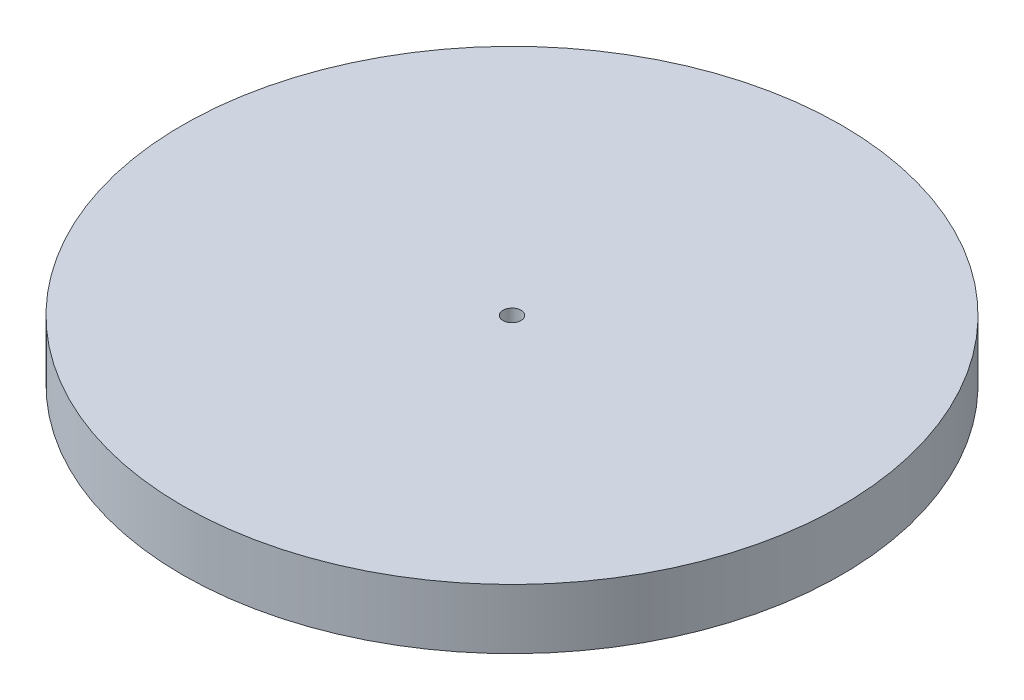
SolidWorks part; units mm, degrees
ref_plane "Front Plane" through (0, 0, 0) normal (0, 0, 1) x (1, 0, 0)
ref_plane "Top Plane" through (0, 0, 0) normal (0, 1, 0) x (1, 0, 0)
ref_plane "Right Plane" through (0, 0, 0) normal (1, 0, 0) x (0, 0, -1)
sketch "Sketch2" plane through (0, 0, 0) normal (0, 1, 0) x (1, 0, 0)
  circle A0 centre (0, 0) radius 12
  dimension "D1" = 24
extrude "Boss-Extrude1" add sketch "Sketch2" along normal blind 5
sketch "Sketch3" plane through (0, 5, 0) normal (0, 1, 0) x (1, 0, 0)
  circle A0 centre (0, 0) radius 0.75
  dimension "D1" = 1.5
extrude "Cut-Extrude1" cut sketch "Sketch3" against normal blind 5
sketch "Sketch4" plane through (0, 5, 0) normal (0, 1, 0) x (1, 0, 0)
  circle A0 centre (0, 0) radius 27.5
  dimension "D1" = 55
extrude "Boss-Extrude2" add sketch "Sketch4" along normal blind 5
sketch "Sketch5" plane through (0, 10, 0) normal (0, 1, 0) x (1, 0, 0)
  circle A0 centre (0, 0) radius 0.75
  dimension "D1" = 1.5
extrude "Cut-Extrude2" cut sketch "Sketch5" against normal blind 15
